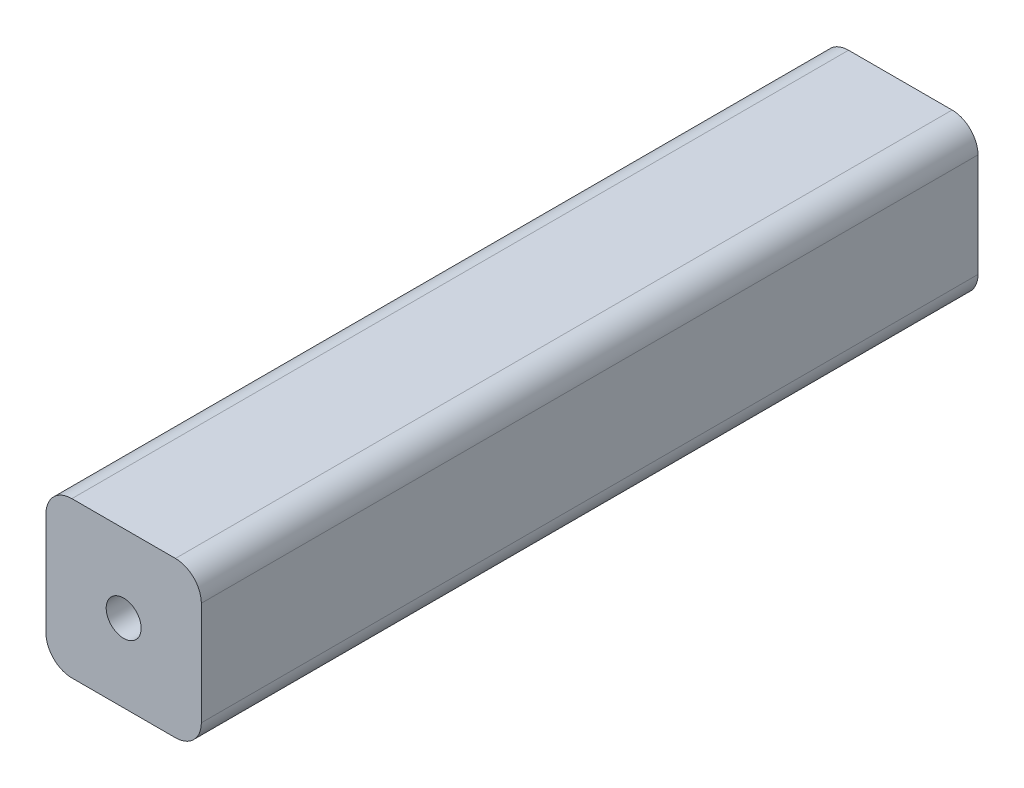
SolidWorks part; units mm, degrees
ref_plane "Front Plane" through (0, 0, 0) normal (0, 0, 1) x (1, 0, 0)
ref_plane "Top Plane" through (0, 0, 0) normal (0, 1, 0) x (1, 0, 0)
ref_plane "Right Plane" through (0, 0, 0) normal (1, 0, 0) x (0, 0, -1)
sketch "Sketch1" plane through (0, 0, 0) normal (0, 0, 1) x (1, 0, 0)
  line L1 (-83, -75.5) -> (-75, -75.5)
  line L2 (-85, -77.5) -> (-85, -85.5)
  line L3 (-83, -87.5) -> (-75, -87.5)
  line L4 (-73, -77.5) -> (-73, -85.5)
  line L6 (-85, -81.5) -> (-73, -81.5) construction
  circle A0 centre (-79, -81.5) radius 1.35
  arc A1 (-75, -75.5) -> (-73, -77.5) centre (-75, -77.5) cw
  arc A2 (-75, -87.5) -> (-73, -85.5) centre (-75, -85.5) ccw
  arc A3 (-85, -85.5) -> (-83, -87.5) centre (-83, -85.5) ccw
  arc A4 (-83, -75.5) -> (-85, -77.5) centre (-83, -77.5) ccw
  dimension "D3" = 2
extrude "Boss-Extrude1" add sketch "Sketch1" along normal blind 60 contours A0 L6 | L6 A0 | L2 A3 L3 A2 L4 A1 L1 A4
